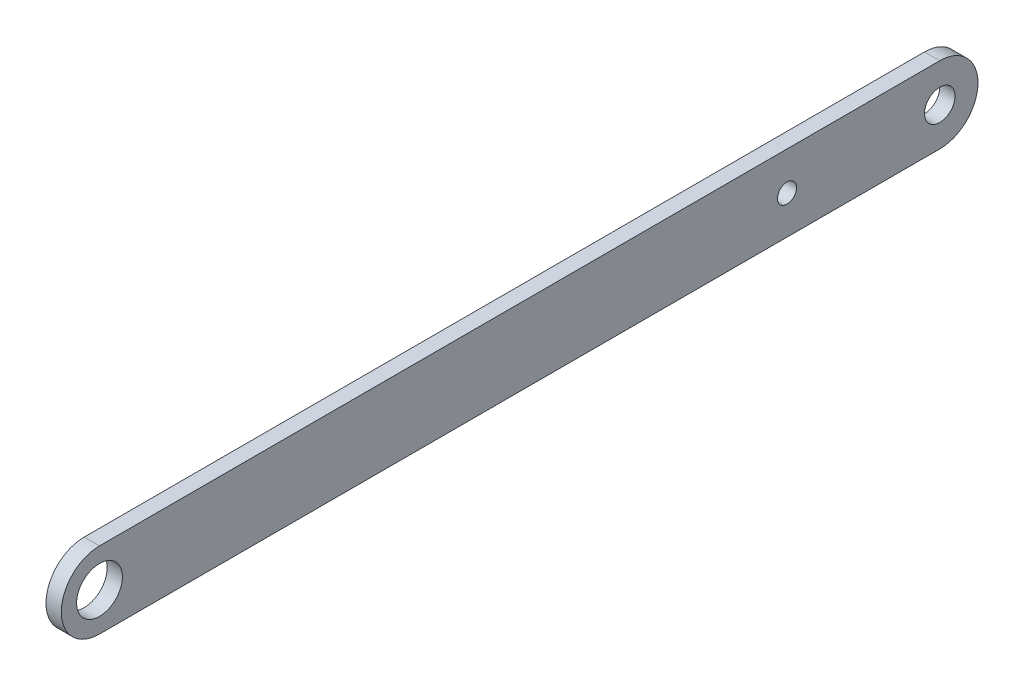
SolidWorks part; units mm, degrees
ref_plane "Front Plane" through (0, 0, 0) normal (0, 0, 1) x (1, 0, 0)
ref_plane "Top Plane" through (0, 0, 0) normal (0, 1, 0) x (1, 0, 0)
ref_plane "Right Plane" through (0, 0, 0) normal (1, 0, 0) x (0, 0, -1)
sketch "Sketch1" plane through (0, 0, 0) normal (1, 0, 0) x (0, 0, -1)
  line L0 (0, 0) -> (110, 0)
  line L1 (0, 10) -> (110, 10)
  line L2 (110, 5) -> (0, 5) construction
  arc A0 (0, 10) -> (0, 0) centre (0, 5) ccw
  arc A1 (110, 10) -> (110, 0) centre (110, 5) cw
  circle A2 centre (0, 5) radius 3
  circle A3 centre (110, 5) radius 2
  circle A4 centre (90, 5) radius 1.25
  dimension "D4" = 5
  dimension "D5" = 5
  dimension "D6" = 6
  dimension "D7" = 4
  dimension "D8" = 2.5
  dimension "D1" = 110
  dimension "D2" = 10
  dimension "D3" = 5
  dimension "D9" = 20
extrude "Boss-Extrude1" add sketch "Sketch1" along normal blind 2
